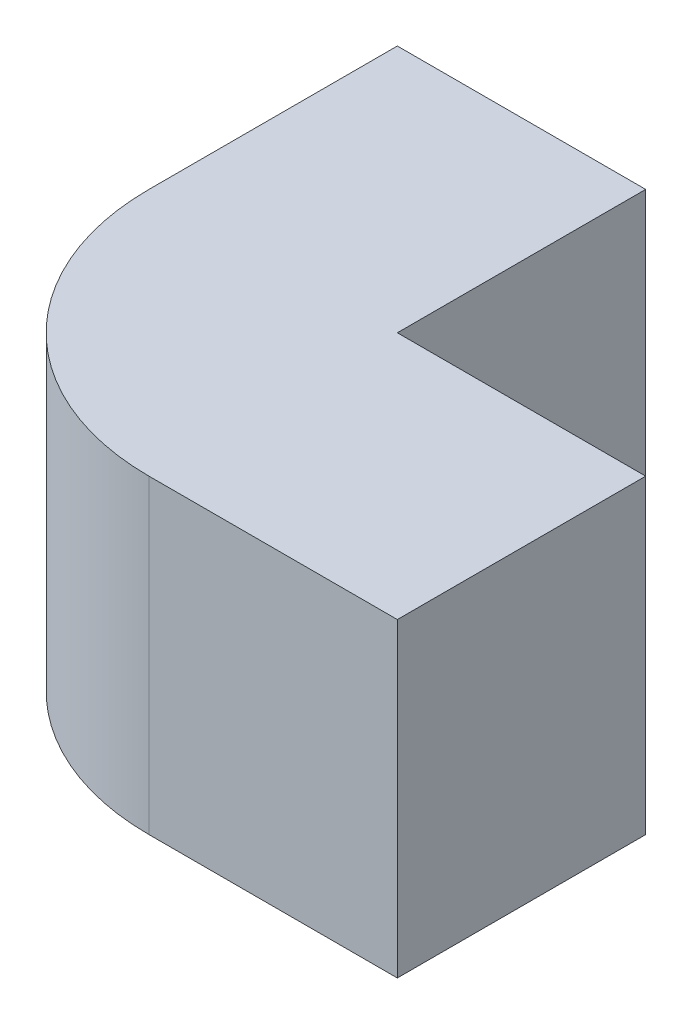
SolidWorks part; units mm, degrees
ref_plane "前视基准面" through (0, 0, 0) normal (0, 0, 1) x (1, 0, 0)
ref_plane "上视基准面" through (0, 0, 0) normal (0, 1, 0) x (1, 0, 0)
ref_plane "右视基准面" through (0, 0, 0) normal (1, 0, 0) x (0, 0, -1)
other "Configuration Table"
sketch "草图1" plane through (0, 0, 0) normal (0, 0, 1) x (1, 0, 0)
  line L1 (0, 0) -> (4, 0)
  line L2 (0, 0) -> (0, -5)
  line L3 (0, -5) -> (4, -5)
  line L4 (4, 0) -> (4, -5)
  dimension "D1" = 4
  dimension "D2" = 5
extrude "凸台-拉伸1" add sketch "草图1" along normal blind 8
sketch "草图2" plane through (4, 0, 0) normal (1, 0, 0) x (0, 0, -1)
  line L1 (-8, 0) -> (-4, 0)
  line L2 (-8, 0) -> (-8, -5)
  line L3 (-8, -5) -> (-4, -5)
  line L4 (-4, 0) -> (-4, -5)
  line L5 (-8, -5) -> (0, -5) construction
extrude "凸台-拉伸2" add sketch "草图2" along normal blind 4
fillet "圆角2" radius 4 1 edges at (0, -2.5, 8)
